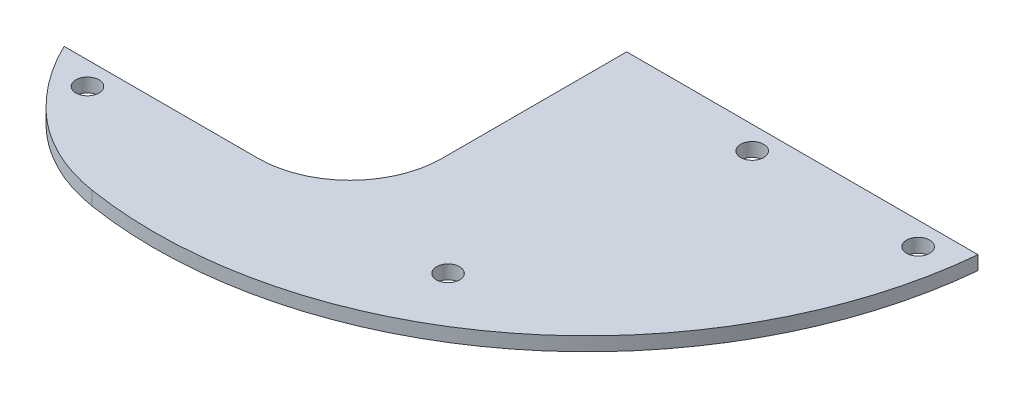
SolidWorks part; units mm, degrees
ref_plane "Front Plane" through (0, 0, 0) normal (0, 0, 1) x (1, 0, 0)
ref_plane "Top Plane" through (0, 0, 0) normal (0, 1, 0) x (1, 0, 0)
ref_plane "Right Plane" through (0, 0, 0) normal (1, 0, 0) x (0, 0, -1)
sketch "Sketch1" plane through (0, 0, 0) normal (0, 1, 0) x (1, 0, 0)
  line L0 (21.1013, 16.7733) -> (-17.0167, 16.7733)
  line L1 (-17.0167, 16.7733) -> (-17.0167, -3.2267)
  line L2 (-27.0167, -13.2267) -> (-33.0167, -13.2267)
  line L3 (-33.0167, -13.2267) -> (-33.0167, -25.2267)
  line L4 (-33.0167, -13.2267) -> (-43.0167, -13.2267)
  line L5 (-43.0167, -13.2267) -> (-43.0167, -20.2267)
  line L7 (-43.0167, -13.2267) -> (-53.0167, -13.2267)
  line L8 (-43.0167, -13.2267) -> (-43.0167, -20.2267)
  line L9 (-43.0167, -20.2267) -> (-53.0167, -20.2267)
  line L10 (-53.0167, -13.2267) -> (-53.0167, -20.2267)
  arc A0 (-33.0167, -25.2267) -> (21.1013, 16.7733) centre (-25.6899, 21.1987) ccw
  arc A2 (-33.0167, -25.2267) -> (-43.0167, -20.2267) centre (-30.1341, -6.9616) cw
  arc A3 (-17.0167, -3.2267) -> (-27.0167, -13.2267) centre (-27.0167, -3.2267) cw
  point P14 (-17.0167, -13.2267)
  dimension "D4" = 10
  dimension "D5" = 7
  dimension "D6" = 20
  dimension "D7" = 10
  dimension "D9" = 47
  dimension "D1" = 12
  dimension "D2" = 16
  dimension "D3" = 38.118
  dimension "D8" = 10
extrude "Pcb Board" add sketch "Sketch1" along normal mid plane 1.5
sketch "Sketch6" plane through (0, 0.75, 0) normal (0, 1, 0) x (1, 0, 0)
  line L0 (-43.0167, -13.2267) -> (-48.0551, -13.2267)
  line L2 (-43.0167, -13.2267) -> (-43.0167, -20.2267)
  line L5 (-27.0167, -13.2267) -> (-43.0167, -13.2267) construction
  arc A0 (-48.0551, -13.2267) -> (-43.0167, -20.2267) centre (-25.8725, -2.5735) ccw
  arc A1 (-43.0167, -20.2267) -> (-33.0167, -25.2267) centre (-30.1341, -6.9616) ccw construction
extrude "Boss-Extrude1" add sketch "Sketch6" against normal up to surface (1.5 mm away)
sketch "Offset Layout" plane through (0, 0.75, 0) normal (0, 1, 0) x (1, 0, 0)
  line L0 (-10, 0) -> (1.8335, -44.1632) construction
  line L1 (0, 23.3189) -> (0, 0) construction
  line L2 (0, 0) -> (32.4024, 0) construction
  line L3 (-10, 0) -> (9.3642, -41.5267) construction
  line L4 (-15.4367, -24.1427) -> (-6.7433, -21.8133)
  line L5 (-15.4367, -24.1427) -> (-19.1895, -10.1367)
  line L6 (-19.1895, -10.1367) -> (-10.4962, -7.8074)
  line L7 (-6.7433, -21.8133) -> (-10.4962, -7.8074)
  line L8 (-15.4367, -24.1427) -> (-10.4962, -7.8074) construction
  line L9 (-19.1895, -10.1367) -> (-6.7433, -21.8133) construction
  line L10 (1.9354, -19.6801) -> (12.8474, -14.5918)
  line L11 (1.9354, -19.6801) -> (-5.0378, -4.726)
  line L12 (-5.0378, -4.726) -> (5.8742, 0.3623)
  line L13 (12.8474, -14.5918) -> (5.8742, 0.3623)
  line L14 (1.9354, -19.6801) -> (5.8742, 0.3623) construction
  line L15 (-5.0378, -4.726) -> (12.8474, -14.5918) construction
  arc A0 (-33.0167, -25.2267) -> (21.1013, 16.7733) centre (-25.6899, 21.1987) ccw construction
  point P9 (-12.9664, -15.975)
  point P17 (3.9048, -9.6589)
  dimension "D1" = 75
  dimension "D2" = 9
  dimension "D3" = 14.5
  dimension "D4" = 2.5
  dimension "D5" = 45.7211
  dimension "D6" = 10
  dimension "D7" = 12.04
  dimension "D8" = 16.5
  dimension "D9" = 2.5
  dimension "D10" = 10
sketch "Middle VERTICALlayout" plane through (0, 0.75, 0) normal (0, 1, 0) x (1, 0, 0)
  line L0 (-25.0551, -13.2267) -> (-25.0551, -31.35) construction
  line L1 (-27.0167, -13.2267) -> (-48.0551, -13.2267) construction
  line L3 (-27.0167, -13.2267) -> (-48.0551, -13.2267) construction
  line L4 (-34.8051, -27.2267) -> (-25.8051, -27.2267)
  line L5 (-34.8051, -27.2267) -> (-34.8051, -16.2267)
  line L6 (-34.8051, -16.2267) -> (-25.8051, -16.2267)
  line L7 (-25.8051, -27.2267) -> (-25.8051, -16.2267)
  line L8 (-34.8051, -27.2267) -> (-25.8051, -16.2267) construction
  line L9 (-34.8051, -16.2267) -> (-25.8051, -27.2267) construction
  line L10 (-24.3051, -27.2267) -> (-12.3051, -27.2267)
  line L11 (-24.3051, -27.2267) -> (-24.3051, -17.2267)
  line L12 (-24.3051, -17.2267) -> (-12.3051, -17.2267)
  line L13 (-12.3051, -27.2267) -> (-12.3051, -17.2267)
  line L14 (-24.3051, -27.2267) -> (-12.3051, -17.2267) construction
  line L15 (-24.3051, -17.2267) -> (-12.3051, -27.2267) construction
  point P7 (-30.3051, -21.7267)
  point P12 (-15.872, -22.5181)
  dimension "D1" = 23
  dimension "D2" = 11
  dimension "D3" = 9
  dimension "D4" = 0.75
  dimension "D5" = 12
  dimension "D6" = 10
  dimension "D7" = 0.75
  dimension "D8" = 8.5
sketch "Sketch5" plane through (0, 0.75, 0) normal (0, 1, 0) x (1, 0, 0)
  line L0 (21.1013, 16.7733) -> (-17.0167, 16.7733) construction
  line L1 (-27.0167, -13.2267) -> (-48.0551, -13.2267) construction
  circle A0 centre (-43.0167, -15.7267) radius 1.25
  circle A1 centre (17.1013, 14.2733) radius 1.25
  circle A2 centre (-5.8987, -13.7267) radius 1.25
  circle A3 centre (-0.8987, 14.2733) radius 1.25
  dimension "D3" = 4
  dimension "D1" = 2.5
  dimension "D4" = 2.5
  dimension "D5" = 18
  dimension "D7" = 28
  dimension "D8" = 23
extrude "Mouting Holes" cut sketch "Sketch5" against normal blind 10
sketch "XL320 connector" plane through (0, 0.75, 0) normal (0, 1, 0) x (1, 0, 0)
  line L0 (21.1013, 16.7733) -> (-17.0167, 16.7733) construction
  line L1 (4.9833, 10.6233) -> (12.9833, 10.6233)
  line L2 (4.9833, 10.6233) -> (4.9833, 14.2733)
  line L3 (4.9833, 14.2733) -> (12.9833, 14.2733)
  line L4 (12.9833, 10.6233) -> (12.9833, 14.2733)
  line L5 (4.9833, 10.6233) -> (12.9833, 14.2733) construction
  line L6 (4.9833, 14.2733) -> (12.9833, 10.6233) construction
  point P0 (8.9833, 12.4483)
  dimension "D1" = 8
  dimension "D2" = 3.65
  dimension "D4" = 2.5
sketch "AX-12A connector" plane through (0, 0.75, 0) normal (0, 1, 0) x (1, 0, 0)
  line L0 (21.1013, 16.7733) -> (-17.0167, 16.7733) construction
  line L1 (3.0833, 1.8733) -> (12.9833, 1.8733)
  line L2 (3.0833, 1.8733) -> (3.0833, 6.7733)
  line L3 (3.0833, 6.7733) -> (12.9833, 6.7733)
  line L4 (12.9833, 1.8733) -> (12.9833, 6.7733)
  line L5 (3.0833, 1.8733) -> (12.9833, 6.7733) construction
  line L6 (3.0833, 6.7733) -> (12.9833, 1.8733) construction
  point P0 (8.0333, 4.3233)
  dimension "D1" = 9.9
  dimension "D2" = 4.9
  dimension "D3" = 10
sketch "Fan Connectors" plane through (0, 0.75, 0) normal (0, 1, 0) x (1, 0, 0)
  line L0 (21.1013, 16.7733) -> (-17.0167, 16.7733) construction
  line L1 (-1.1487, -3.9267) -> (6.1013, -3.9267)
  line L2 (-1.1487, -3.9267) -> (-1.1487, -0.2267)
  line L3 (-1.1487, -0.2267) -> (6.1013, -0.2267)
  line L4 (6.1013, -3.9267) -> (6.1013, -0.2267)
  line L5 (-1.1487, -3.9267) -> (6.1013, -0.2267) construction
  line L6 (-1.1487, -0.2267) -> (6.1013, -3.9267) construction
  line L7 (-1.1487, -10.1267) -> (6.1013, -10.1267)
  line L8 (-1.1487, -10.1267) -> (-1.1487, -6.4267)
  line L9 (-1.1487, -6.4267) -> (6.1013, -6.4267)
  line L10 (6.1013, -10.1267) -> (6.1013, -6.4267)
  line L11 (-1.1487, -10.1267) -> (6.1013, -6.4267) construction
  line L12 (-1.1487, -6.4267) -> (6.1013, -10.1267) construction
  point P0 (2.4763, -2.0767)
  point P5 (2.4763, -8.2767)
  dimension "D1" = 7.25
  dimension "D2" = 3.7
  dimension "D3" = 17
  dimension "D4" = 2.5
  dimension "D5" = 15
